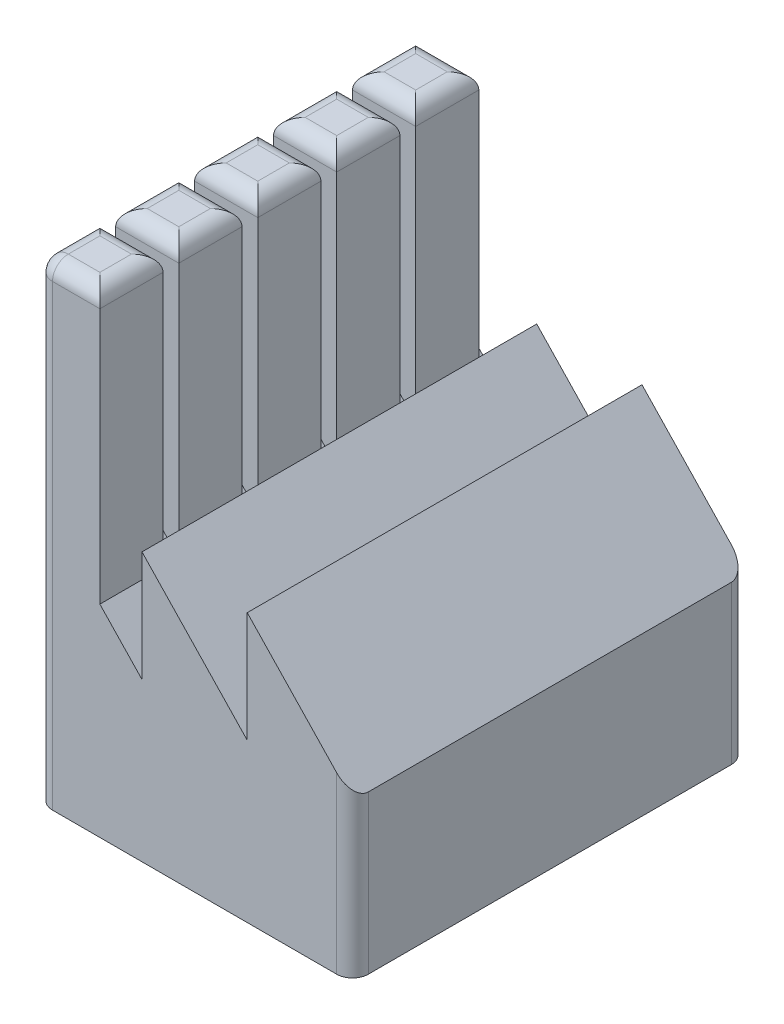
SolidWorks part; units mm, degrees
ref_plane "前视基准面" through (0, 0, 0) normal (0, 0, 1) x (1, 0, 0)
ref_plane "上视基准面" through (0, 0, 0) normal (0, 1, 0) x (1, 0, 0)
ref_plane "右视基准面" through (0, 0, 0) normal (1, 0, 0) x (0, 0, -1)
sketch "草图1" plane through (0, 0, 0) normal (0, 0, 1) x (1, 0, 0)
  line L0 (-10, 5) -> (-10, 12)
  line L1 (-10, -5) -> (10, -5)
  line L2 (-10, -5) -> (-10, 5)
  line L4 (10, -5) -> (10, 5)
  line L5 (-10, -5) -> (10, 5) construction
  line L6 (-10, 5) -> (10, -5) construction
  line L7 (-10, 12) -> (-3.3333, 5)
  line L8 (-3.3333, 5) -> (-3.3333, 12)
  line L9 (-3.3333, 12) -> (3.3333, 5)
  line L10 (3.3333, 5) -> (3.3333, 12)
  line L11 (3.3333, 12) -> (10, 5)
  line L12 (-10, 5) -> (-3.3333, 5) construction
  line L13 (3.3333, 5) -> (-3.3333, 5) construction
  line L14 (3.3333, 5) -> (10, 5) construction
  point P0 (0, 0)
  dimension "D1" = 10
  dimension "D2" = 20
  dimension "D3" = 7
extrude "凸台-拉伸1" add sketch "草图1" along normal blind 25
sketch "草图2" plane through (0, -5, 0) normal (0, -1, 0) x (1, 0, 0)
  line L1 (-10, 25) -> (-6, 25)
  line L2 (-10, 25) -> (-10, 21)
  line L3 (-10, 21) -> (-6, 21)
  line L4 (-6, 25) -> (-6, 21)
  dimension "D1" = 4
extrude "凸台-拉伸2" add sketch "草图2" against normal blind 30
sketch3d "3D草图1"
  line L0 (-2.5, 25, 42.5) -> (-2.5, 40, 42.5) construction
  line L1 (-10, 25, 21) -> (5, 25, 64) construction
  line L6 (-10, 25, 21) -> (-10, 25, 25)
  line L7 (-10, 25, 25) -> (-6, 25, 25)
  line L8 (-6, 25, 21) -> (-6, 25, 25)
  line L9 (-6, 25, 21) -> (-10, 25, 21)
  line L10 (-10, 25, 21) -> (-10, 25, 25)
  line L11 (-10, 25, 25) -> (-6, 25, 25)
  line L12 (-6, 25, 21) -> (-6, 25, 25)
  line L13 (-6, 25, 21) -> (-10, 25, 21)
  circle A0 centre (-2.5, 40, 42.5) radius 3.75
  point P8 (-2.5, 43.75, 42.5)
  dimension "D1" = 7.5
  dimension "D2" = 15
  dimension "D3" = 0
loft "放样1" [suppressed] add
pattern_linear "阵列(线性)1" count 5 spacing 5 along (0, 0, -1) of "凸台-拉伸2"
fillet "圆角1" radius 1 25 edges at (-10, 12, 0.5) (-10, 25, 3) (-8, 25, 5) (-6, 25, 3) (-8, 25, 1) (-10, 10, 25) (10, 0, 25) (-8, 25, 25) (-8, 25, 21) (-10, 25, 23) (-6, 25, 23) (-10, 25, 18) (-8, 25, 20) (-6, 25, 18) (-8, 25, 16) (-10, 25, 13) (-8, 25, 15) (-6, 25, 13) (-8, 25, 11) (10, 0, 0) (-10, 25, 8) (-8, 25, 10) (-6, 25, 8) (-8, 25, 6) (-10, 3.5, 0)
